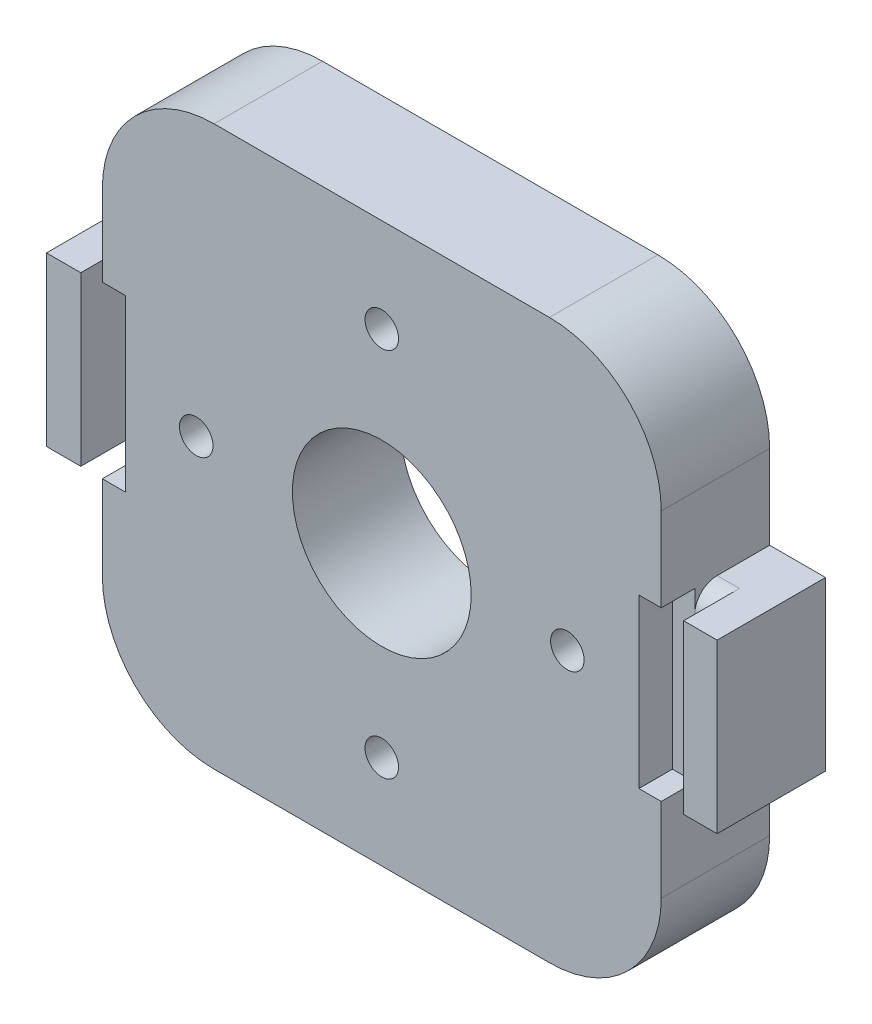
SolidWorks part; units mm, degrees
ref_plane "Front Plane" through (0, 0, 0) normal (0, 0, 1) x (1, 0, 0)
ref_plane "Top Plane" through (0, 0, 0) normal (0, 1, 0) x (1, 0, 0)
ref_plane "Right Plane" through (0, 0, 0) normal (1, 0, 0) x (0, 0, -1)
sketch "Sketch1" plane through (0, 0, 0) normal (0, 0, 1) x (1, 0, 0)
  line L0 (0, 0) -> (18.1, 0)
  line L1 (-25, -25) -> (25, -25)
  line L2 (-25, -25) -> (-25, 25)
  line L3 (-25, 25) -> (25, 25)
  line L4 (25, -25) -> (25, 25)
  line L5 (-25, -25) -> (25, 25) construction
  line L6 (-25, 25) -> (25, -25) construction
  circle A0 centre (0, 0) radius 8
  circle A1 centre (16.6, 0) radius 1.5
  circle A2 centre (0, -16.6) radius 1.5
  circle A3 centre (-16.6, 0) radius 1.5
  circle A4 centre (0, 16.6) radius 1.5
  point P19 (0, 0)
  dimension "D1" = 16
  dimension "D3" = 3
  dimension "D2" = 50
  dimension "D4" = 18.1
  dimension "D5" = 4
extrude "Boss-Extrude1" add sketch "Sketch1" along normal blind 9.7
sketch "Sketch2" plane through (0, 0, 9.7) normal (0, 0, 1) x (1, 0, 0)
  line L0 (-19.95, 0) -> (-13.25, 0)
  line L1 (-16.6, -3) -> (-16.6, 3)
  line L2 (-19.95, -0.2183) -> (-19.95, 0.2183) construction
  line L4 (-19.0252, 0) -> (-20.8748, 0) construction
  line L5 (-18.464, 2.792) -> (-18.086, 3.0103) construction
  line L6 (-17.8126, 2.1003) -> (-18.7374, 3.7021) construction
  line L7 (-15.114, 3.0103) -> (-14.736, 2.792) construction
  line L8 (-15.3874, 2.1003) -> (-14.4626, 3.7021) construction
  line L9 (-13.25, 0.2183) -> (-13.25, -0.2183) construction
  line L10 (-14.1748, 0) -> (-12.3252, 0) construction
  line L11 (-14.736, -2.792) -> (-15.114, -3.0103) construction
  line L12 (-15.3874, -2.1003) -> (-14.4626, -3.7021) construction
  line L13 (-18.086, -3.0103) -> (-18.464, -2.792) construction
  line L14 (-17.8126, -2.1003) -> (-18.7374, -3.7021) construction
  line L15 (-19.95, 0) -> (-18.275, -2.9012)
  line L17 (-18.275, -2.9012) -> (-14.925, -2.9012)
  line L18 (-14.925, -2.9012) -> (-13.25, 0)
  line L20 (-13.25, 0) -> (-14.925, 2.9012)
  line L22 (-14.925, 2.9012) -> (-18.275, 2.9012)
  line L23 (-18.275, 2.9012) -> (-19.95, 0)
  line L26 (-2.8059, 14.8297) -> (0.0953, 13.1547)
  line L27 (0.0953, 19.8547) -> (0.0953, 13.1547)
  line L28 (0.0953, 19.8547) -> (-2.8059, 18.1797)
  line L29 (-2.8059, 18.1797) -> (-2.8059, 14.8297)
  line L30 (2.9964, 14.8297) -> (2.9964, 18.1797)
  line L31 (0.0953, 13.1547) -> (2.9964, 14.8297)
  line L32 (2.9964, 18.1797) -> (0.0953, 19.8547)
  line L33 (14.925, 2.7107) -> (13.25, -0.1905)
  line L34 (19.95, -0.1905) -> (13.25, -0.1905)
  line L35 (19.95, -0.1905) -> (18.275, 2.7107)
  line L36 (18.275, 2.7107) -> (14.925, 2.7107)
  line L37 (14.925, -3.0917) -> (18.275, -3.0917)
  line L38 (13.25, -0.1905) -> (14.925, -3.0917)
  line L39 (18.275, -3.0917) -> (19.95, -0.1905)
  line L40 (2.8059, -15.0203) -> (-0.0953, -13.3453)
  line L41 (-0.0953, -20.0453) -> (-0.0953, -13.3453)
  line L42 (-0.0953, -20.0453) -> (2.8059, -18.3703)
  line L43 (2.8059, -18.3703) -> (2.8059, -15.0203)
  line L44 (-2.9964, -15.0203) -> (-2.9964, -18.3703)
  line L45 (-0.0953, -13.3453) -> (-2.9964, -15.0203)
  line L46 (-2.9964, -18.3703) -> (-0.0953, -20.0453)
  circle A2 centre (-16.6, 0) radius 1.5 construction
  circle A3 centre (-16.6, 0) radius 1.5
  circle A4 centre (-16.6, 0) radius 3.35 construction
  point P5 (-16.6, 0)
  point P8 (-16.6, 0)
  point P25 (-19.95, 0)
  point P63 (-19.95, 0)
  point P143 (0, -0.0953)
  dimension "D3" = 6.7
  dimension "D1" = 5.8024
  dimension "D4" = 6
  dimension "D5" = 4
sketch "Sketch6" plane through (0, 0, 9.7) normal (0, 0, 1) x (1, 0, 0)
  line L0 (-18.275, -2.9012) -> (-14.925, -2.9012) construction
  line L1 (-19.95, 0) -> (-18.275, -2.9012) construction
  line L2 (-18.275, 2.9012) -> (-19.95, 0) construction
  line L3 (-14.925, 2.9012) -> (-18.275, 2.9012) construction
  line L4 (-13.25, 0) -> (-14.925, 2.9012) construction
  line L5 (-14.925, -2.9012) -> (-13.25, 0) construction
  line L6 (2.8059, -18.3703) -> (2.8059, -15.0203) construction
  line L7 (-0.0953, -20.0453) -> (-0.0953, -13.3453) construction
  line L8 (-0.0953, -20.0453) -> (2.8059, -18.3703) construction
  line L9 (-2.9964, -18.3703) -> (-0.0953, -20.0453) construction
  line L10 (-2.9964, -15.0203) -> (-2.9964, -18.3703) construction
  line L11 (-0.0953, -13.3453) -> (-2.9964, -15.0203) construction
  line L12 (2.8059, -15.0203) -> (-0.0953, -13.3453) construction
  line L13 (14.925, -3.0917) -> (18.275, -3.0917) construction
  line L14 (19.95, -0.1905) -> (13.25, -0.1905) construction
  line L15 (18.275, -3.0917) -> (19.95, -0.1905) construction
  line L16 (19.95, -0.1905) -> (18.275, 2.7107) construction
  line L17 (18.275, 2.7107) -> (14.925, 2.7107) construction
  line L18 (14.925, 2.7107) -> (13.25, -0.1905) construction
  line L19 (13.25, -0.1905) -> (14.925, -3.0917) construction
  line L20 (0.0953, 19.8547) -> (-2.8059, 18.1797) construction
  line L21 (-2.8059, 18.1797) -> (-2.8059, 14.8297) construction
  line L22 (2.9964, 18.1797) -> (0.0953, 19.8547) construction
  line L23 (0.0953, 19.8547) -> (0.0953, 13.1547) construction
  line L24 (2.9964, 14.8297) -> (2.9964, 18.1797) construction
  line L25 (0.0953, 13.1547) -> (2.9964, 14.8297) construction
  line L26 (-2.8059, 14.8297) -> (0.0953, 13.1547) construction
  line L27 (-18.275, -2.9012) -> (-14.925, -2.9012)
  line L28 (-19.95, 0) -> (-18.275, -2.9012)
  line L29 (-18.275, 2.9012) -> (-19.95, 0)
  line L30 (-14.925, 2.9012) -> (-18.275, 2.9012)
  line L31 (-13.25, 0) -> (-14.925, 2.9012)
  line L32 (-14.925, -2.9012) -> (-13.25, 0)
  line L33 (2.8059, -18.3703) -> (2.8059, -15.0203)
  line L34 (-0.0953, -20.0453) -> (-0.0953, -13.3453)
  line L35 (-0.0953, -20.0453) -> (2.8059, -18.3703)
  line L36 (-2.9964, -18.3703) -> (-0.0953, -20.0453)
  line L37 (-2.9964, -15.0203) -> (-2.9964, -18.3703)
  line L38 (-0.0953, -13.3453) -> (-2.9964, -15.0203)
  line L39 (2.8059, -15.0203) -> (-0.0953, -13.3453)
  line L40 (14.925, -3.0917) -> (18.275, -3.0917)
  line L41 (19.95, -0.1905) -> (13.25, -0.1905)
  line L42 (18.275, -3.0917) -> (19.95, -0.1905)
  line L43 (19.95, -0.1905) -> (18.275, 2.7107)
  line L44 (18.275, 2.7107) -> (14.925, 2.7107)
  line L45 (14.925, 2.7107) -> (13.25, -0.1905)
  line L46 (13.25, -0.1905) -> (14.925, -3.0917)
  line L47 (0.0953, 19.8547) -> (-2.8059, 18.1797)
  line L48 (-2.8059, 18.1797) -> (-2.8059, 14.8297)
  line L49 (2.9964, 18.1797) -> (0.0953, 19.8547)
  line L50 (0.0953, 19.8547) -> (0.0953, 13.1547)
  line L51 (2.9964, 14.8297) -> (2.9964, 18.1797)
  line L52 (0.0953, 13.1547) -> (2.9964, 14.8297)
  line L53 (-2.8059, 14.8297) -> (0.0953, 13.1547)
  circle A0 centre (16.6, 0) radius 1.5 construction
  circle A1 centre (0, -16.6) radius 1.5 construction
  circle A2 centre (0, 16.6) radius 1.5 construction
  circle A3 centre (-16.6, 0) radius 1.5 construction
  circle A4 centre (16.6, 0) radius 1.5
  circle A5 centre (0, -16.6) radius 1.5
  circle A6 centre (0, 16.6) radius 1.5
  circle A7 centre (-16.6, 0) radius 1.5
  point P0 (-2.8059, 18.1797)
fillet "Fillet2" radius 10 4 edges at (-25, -25, 4.85) (25, -25, 4.85) (25, 25, 4.85) (-25, 25, 4.85)
sketch "Sketch7" plane through (25, 0, 0) normal (1, 0, 0) x (0, 0, -1)
  line L0 (0, -15) -> (0, 15) construction
  line L2 (-9.7, 7.5) -> (-9.7, -7.5)
  line L5 (0, -15) -> (0, 15)
  line L10 (-9.7, -15) -> (-9.7, 15) construction
  line L11 (-9.7, 7.5) -> (0, 7.5)
  line L12 (-9.7, 7.5) -> (-9.7, -7.5)
  line L13 (-9.7, -7.5) -> (0, -7.5)
  line L14 (0, 7.5) -> (0, -7.5)
  point P6 (-9.7, 0)
  line M25 (-9.7, 15) -> (-9.7, -15)
  dimension "D1" = 15
  dimension "D2" = 0
sketch "Sketch9" plane through (0, 0, 0) normal (0, 0, -1) x (-1, 0, 0)
  line L0 (2.9964, -15.0203) -> (2.9964, -18.3703) construction
  line L1 (0.0953, -13.3453) -> (2.9964, -15.0203) construction
  line L2 (-2.8059, -15.0203) -> (0.0953, -13.3453) construction
  line L3 (-2.8059, -18.3703) -> (-2.8059, -15.0203) construction
  line L4 (0.0953, -20.0453) -> (-2.8059, -18.3703) construction
  line L5 (2.9964, -18.3703) -> (0.0953, -20.0453) construction
  line L6 (18.275, -2.9012) -> (14.925, -2.9012) construction
  line L7 (19.95, 0) -> (18.275, -2.9012) construction
  line L8 (18.275, 2.9012) -> (19.95, 0) construction
  line L9 (14.925, 2.9012) -> (18.275, 2.9012) construction
  line L10 (13.25, 0) -> (14.925, 2.9012) construction
  line L11 (14.925, -2.9012) -> (13.25, 0) construction
  line L12 (2.8059, 14.8297) -> (-0.0953, 13.1547) construction
  line L13 (2.8059, 18.1797) -> (2.8059, 14.8297) construction
  line L14 (-0.0953, 19.8547) -> (2.8059, 18.1797) construction
  line L15 (-2.9964, 18.1797) -> (-0.0953, 19.8547) construction
  line L16 (-2.9964, 14.8297) -> (-2.9964, 18.1797) construction
  line L17 (-0.0953, 13.1547) -> (-2.9964, 14.8297) construction
  line L18 (-13.25, -0.1905) -> (-14.925, -3.0917) construction
  line L19 (-14.925, 2.7107) -> (-13.25, -0.1905) construction
  line L20 (-18.275, 2.7107) -> (-14.925, 2.7107) construction
  line L21 (-19.95, -0.1905) -> (-18.275, 2.7107) construction
  line L22 (-18.275, -3.0917) -> (-19.95, -0.1905) construction
  line L23 (-14.925, -3.0917) -> (-18.275, -3.0917) construction
  line L24 (2.9964, -15.0203) -> (2.9964, -18.3703)
  line L25 (0.0953, -13.3453) -> (2.9964, -15.0203)
  line L26 (-2.8059, -15.0203) -> (0.0953, -13.3453)
  line L27 (-2.8059, -18.3703) -> (-2.8059, -15.0203)
  line L28 (0.0953, -20.0453) -> (-2.8059, -18.3703)
  line L29 (2.9964, -18.3703) -> (0.0953, -20.0453)
  line L30 (18.275, -2.9012) -> (14.925, -2.9012)
  line L31 (19.95, 0) -> (18.275, -2.9012)
  line L32 (18.275, 2.9012) -> (19.95, 0)
  line L33 (14.925, 2.9012) -> (18.275, 2.9012)
  line L34 (13.25, 0) -> (14.925, 2.9012)
  line L35 (14.925, -2.9012) -> (13.25, 0)
  line L36 (2.8059, 14.8297) -> (-0.0953, 13.1547)
  line L37 (2.8059, 18.1797) -> (2.8059, 14.8297)
  line L38 (-0.0953, 19.8547) -> (2.8059, 18.1797)
  line L39 (-2.9964, 18.1797) -> (-0.0953, 19.8547)
  line L40 (-2.9964, 14.8297) -> (-2.9964, 18.1797)
  line L41 (-0.0953, 13.1547) -> (-2.9964, 14.8297)
  line L42 (-13.25, -0.1905) -> (-14.925, -3.0917)
  line L43 (-14.925, 2.7107) -> (-13.25, -0.1905)
  line L44 (-18.275, 2.7107) -> (-14.925, 2.7107)
  line L45 (-19.95, -0.1905) -> (-18.275, 2.7107)
  line L46 (-18.275, -3.0917) -> (-19.95, -0.1905)
  line L47 (-14.925, -3.0917) -> (-18.275, -3.0917)
extrude "Cut-Extrude1" cut sketch "Sketch9" against normal blind 2.5
extrude "Boss-Extrude2" add sketch "Sketch7" along normal blind 5 contours L13 L5 L11 M25
sketch "Sketch10" plane through (0, 0, 9.7) normal (0, 0, 1) x (1, 0, 0)
  line L5 (25, 7.5) -> (25, -7.5) construction
  line L6 (23, 7.5) -> (27, 7.5)
  line L8 (23, 7.5) -> (23, -7.5)
  line L13 (23, -7.5) -> (27, -7.5)
  line L14 (27, 7.5) -> (27, -7.5)
  line L15 (23, 7.5) -> (27, -7.5) construction
  line L16 (23, -7.5) -> (27, 7.5) construction
  line L17 (30, -7.5) -> (25, -7.5) construction
  line L19 (0, 0) -> (0.0953, 19.8547) construction
  line L20 (-23.0709, -7.279) -> (-26.9268, 7.7587) construction
  line L21 (-22.927, 7.7204) -> (-27.0707, -7.2406) construction
  line L22 (-26.9268, 7.7587) -> (-27.0707, -7.2406)
  line L23 (-23.0709, -7.279) -> (-27.0707, -7.2406)
  line L24 (-22.927, 7.7204) -> (-23.0709, -7.279)
  line L25 (-22.927, 7.7204) -> (-26.9268, 7.7587)
  point P0 (25, 0)
  point P17 (-24.9988, 0.2399)
  dimension "D1" = 4
extrude "Cut-Extrude2" cut sketch "Sketch10" against normal blind 3
fillet "Fillet3" radius 2 2 edges at (26, -7.5, 6.7) (26, 7.5, 6.7)
pattern_circular "CirPattern9" count 2 every 180 about axis through (0, 0, 0) along (0, 0, 1) of "Boss-Extrude2"
sketch "Sketch11" plane through (0, 0, 9.7) normal (0, 0, 1) x (1, 0, 0)
  line L0 (-30, -7.5) -> (-25, -7.5) construction
  line L1 (-22.927, 7.7204) -> (-26.927, 7.7204)
  line L2 (-22.927, 7.7204) -> (-22.927, -7.5)
  line L3 (-22.927, -7.5) -> (-26.927, -7.5)
  line L4 (-26.927, 7.7204) -> (-26.927, -7.5)
  dimension "D1" = 4
extrude "Cut-Extrude3" cut sketch "Sketch11" against normal blind 4
fillet "Fillet5" radius 2 2 edges at (-25.9635, 7.5, 5.7) (-25.9635, -7.5, 5.7)
